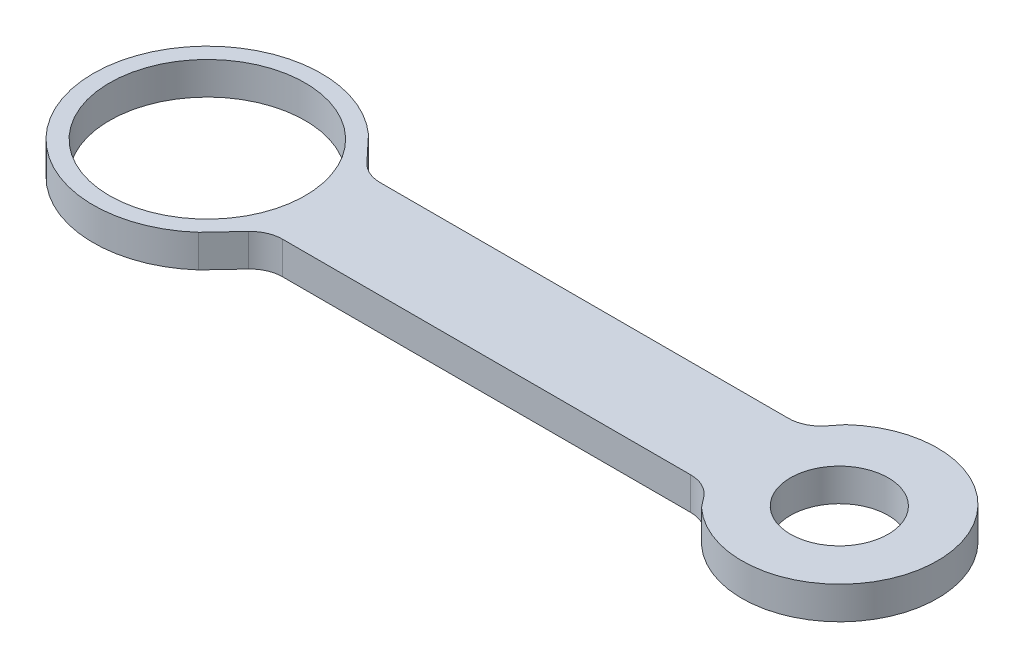
SolidWorks part; units mm, degrees
ref_plane "Front Plane" through (0, 0, 0) normal (0, 0, 1) x (1, 0, 0)
ref_plane "Top Plane" through (0, 0, 0) normal (0, 1, 0) x (1, 0, 0)
ref_plane "Right Plane" through (0, 0, 0) normal (1, 0, 0) x (0, 0, -1)
sketch "Sketch1" plane through (0, 0, 0) normal (0, 1, 0) x (1, 0, 0)
  line L0 (42.3954, 14.5042) -> (45.0142, 17.8129)
  line L1 (-90.6074, 10.7104) -> (34.5543, 10.7104)
  line L3 (-90.6074, -19.2896) -> (34.5543, -19.2896)
  line L5 (64.6933, -4.2896) -> (65.9049, -4.2896) construction
  line L7 (-97.8975, 13.8654) -> (-105.3104, 21.7604)
  line L8 (-105.3104, -30.3396) -> (-97.8975, -22.4447)
  line L10 (42.3954, -23.0834) -> (45.0142, -26.3921)
  arc A0 (-105.3104, 21.7604) -> (-105.3104, -30.3396) centre (-128.6855, -4.2896) ccw
  arc A1 (-90.6074, 10.7104) -> (-97.8975, 13.8654) centre (-90.6074, 20.7104) cw
  arc A2 (-90.6074, -19.2896) -> (-97.8975, -22.4447) centre (-90.6074, -29.2896) ccw
  circle A7 centre (65.2991, -4.2896) radius 0.6058
  arc A8 (45.0142, -26.3921) -> (45.0142, 17.8129) centre (65.2991, -4.2896) ccw
  arc A9 (42.3954, -23.0834) -> (34.5543, -19.2896) centre (34.5543, -29.2896) ccw
  arc A10 (42.3954, 14.5042) -> (34.5543, 10.7104) centre (34.5543, 20.7104) cw
  point P0 (0, 0)
  point P21 (39.3926, -19.2896)
  point P26 (39.3926, 10.7104)
  dimension "D1" = 10
  dimension "D2" = 10
  dimension "D3" = 30
  dimension "D4" = 10
  dimension "D5" = 30
  dimension "D6" = 35
  dimension "D7" = 130
  dimension "D8" = 130
extrude "Boss-Extrude1" add sketch "Sketch1" along normal blind 10
sketch "Sketch3" plane through (0, 10, 0) normal (0, 1, 0) x (1, 0, 0)
  circle A0 centre (-128.6855, -4.2896) radius 30
  circle A1 centre (65.6642, -4.773) radius 15
  circle A2 centre (65.2991, -4.2896) radius 0.6058 construction
  dimension "D1" = 60
  dimension "D2" = 30
extrude "Cut-Extrude1" cut sketch "Sketch3" against normal blind 10
